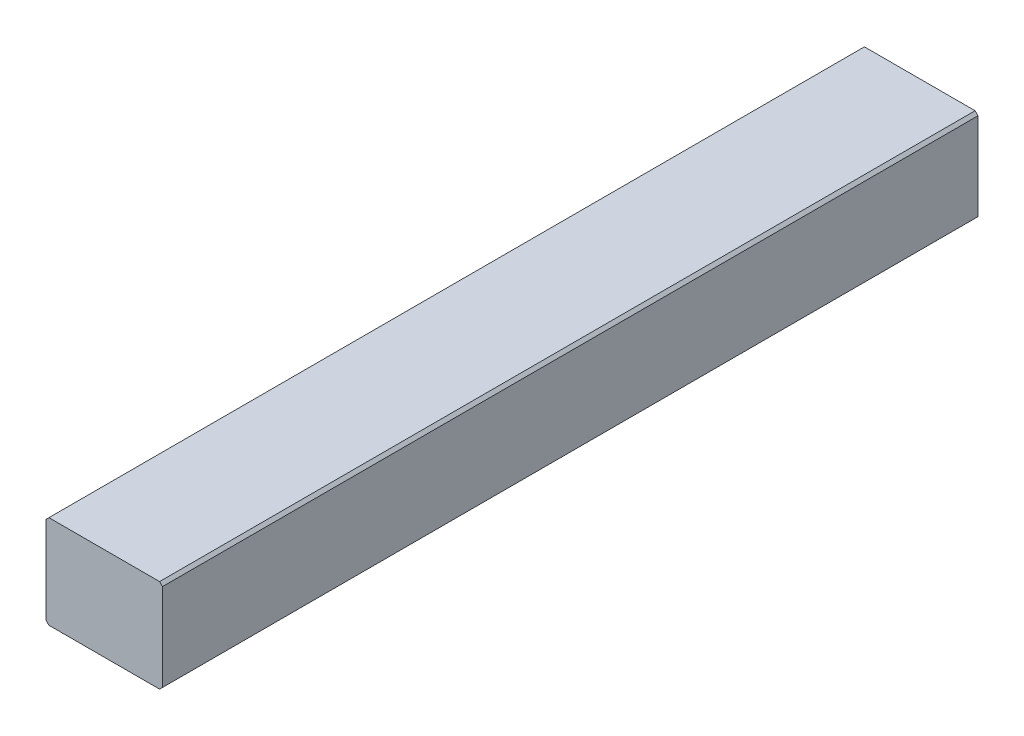
SolidWorks part; units mm, degrees
material "AISI Type 316L stainless steel"
ref_plane "Front Plane" through (0, 0, 0) normal (0, 0, 1) x (1, 0, 0)
ref_plane "Top Plane" through (0, 0, 0) normal (0, 1, 0) x (1, 0, 0)
ref_plane "Right Plane" through (0, 0, 0) normal (1, 0, 0) x (0, 0, -1)
sketch "Sketch1" plane through (0, 0, 0) normal (0, 0, 1) x (1, 0, 0)
  line L1 (-5, 4) -> (5, 4)
  line L2 (-5, 4) -> (-5, -4)
  line L3 (-5, -4) -> (5, -4)
  line L4 (5, 4) -> (5, -4)
  line L5 (-5, 4) -> (5, -4) construction
  line L6 (-5, -4) -> (5, 4) construction
  point P0 (0, 0)
  dimension "D1" = 10
  dimension "D2" = 8
extrude "Extrude1" add sketch "Sketch1" along normal blind 70
chamfer "Chamfer1" distance 0.25 angle 45 4 edges at (-5, -4, 35) (-5, 4, 35) (5, -4, 35) (5, 4, 35)
